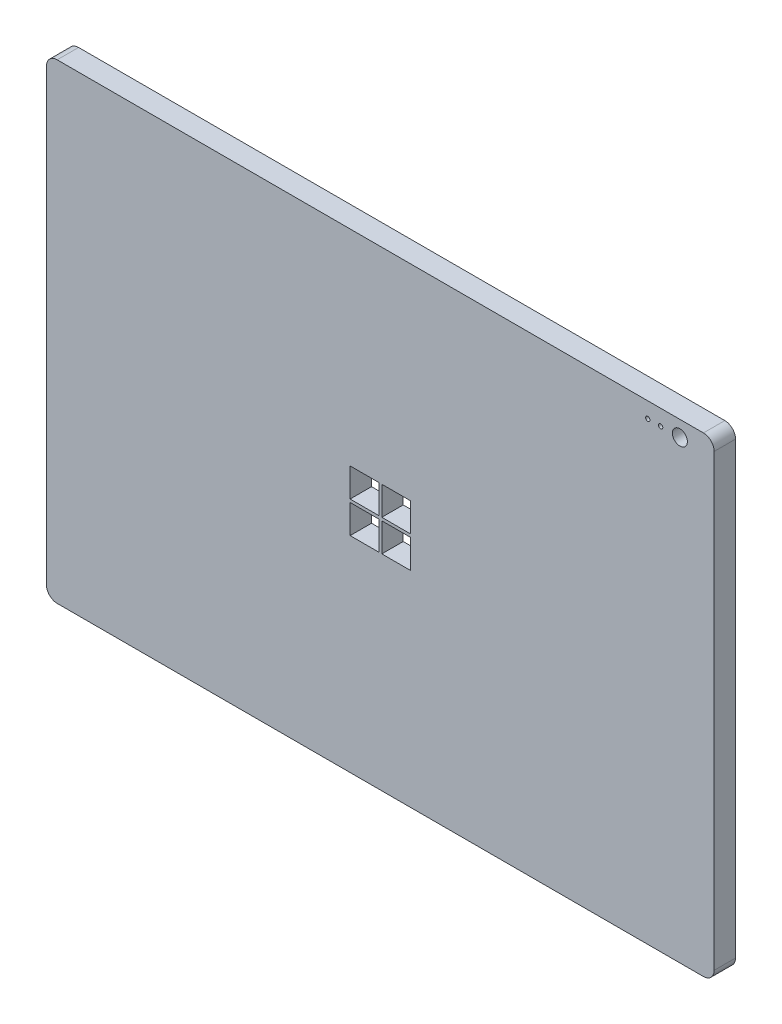
SolidWorks part; units mm, degrees
ref_plane "Front Plane" through (0, 0, 0) normal (0, 0, 1) x (1, 0, 0)
ref_plane "Top Plane" through (0, 0, 0) normal (0, 1, 0) x (1, 0, 0)
ref_plane "Right Plane" through (0, 0, 0) normal (1, 0, 0) x (0, 0, -1)
sketch "Sketch1" plane through (0, 0, 0) normal (0, 0, 1) x (1, 0, 0)
  line L0 (156.7, 95.9) -> (155.3, 95.9) construction
  line L1 (0, 0) -> (312, 0)
  line L2 (0, 0) -> (0, 220)
  line L3 (0, 220) -> (312, 220)
  line L4 (312, 0) -> (312, 220)
  line L5 (141.9, 124.1) -> (155.3, 124.1)
  line L6 (141.9, 124.1) -> (141.9, 110.7)
  line L7 (141.9, 110.7) -> (155.3, 110.7)
  line L8 (155.3, 124.1) -> (155.3, 110.7)
  line L9 (156.7, 124.1) -> (170.1, 124.1)
  line L10 (156.7, 124.1) -> (156.7, 110.7)
  line L11 (156.7, 110.7) -> (170.1, 110.7)
  line L12 (170.1, 124.1) -> (170.1, 110.7)
  line L13 (141.9, 109.3) -> (155.3, 109.3)
  line L14 (141.9, 109.3) -> (141.9, 95.9)
  line L15 (141.9, 95.9) -> (155.3, 95.9)
  line L16 (155.3, 109.3) -> (155.3, 95.9)
  line L17 (156.7, 109.3) -> (170.1, 109.3)
  line L18 (156.7, 109.3) -> (156.7, 95.9)
  line L19 (156.7, 95.9) -> (170.1, 95.9)
  line L20 (170.1, 109.3) -> (170.1, 95.9)
  line L21 (156, 95.9) -> (156, 0) construction
  line L22 (170.1, 110.7) -> (170.1, 109.3) construction
  line L23 (170.1, 110) -> (312, 110) construction
  line L24 (281, 212.7) -> (296, 212.7) construction
  circle A0 centre (296, 212.7) radius 3.5
  circle A1 centre (287, 212.7) radius 1
  circle A2 centre (281, 212.7) radius 1
  point P31 (247.4172, 204.6797)
  dimension "D7" = 7
  dimension "D11" = 2
  dimension "D1" = 312
  dimension "D2" = 220
  dimension "D3" = 1.4
  dimension "D4" = 1.4
  dimension "D5" = 13.4
  dimension "D6" = 16
  dimension "D8" = 7.3
  dimension "D9" = 25
  dimension "D10" = 31
extrude "Boss-Extrude1" add sketch "Sketch1" along normal blind 10
fillet "Fillet1" radius 5 4 edges at (0, 220, 5) (0, 0, 5) (312, 0, 5) (312, 220, 5)
